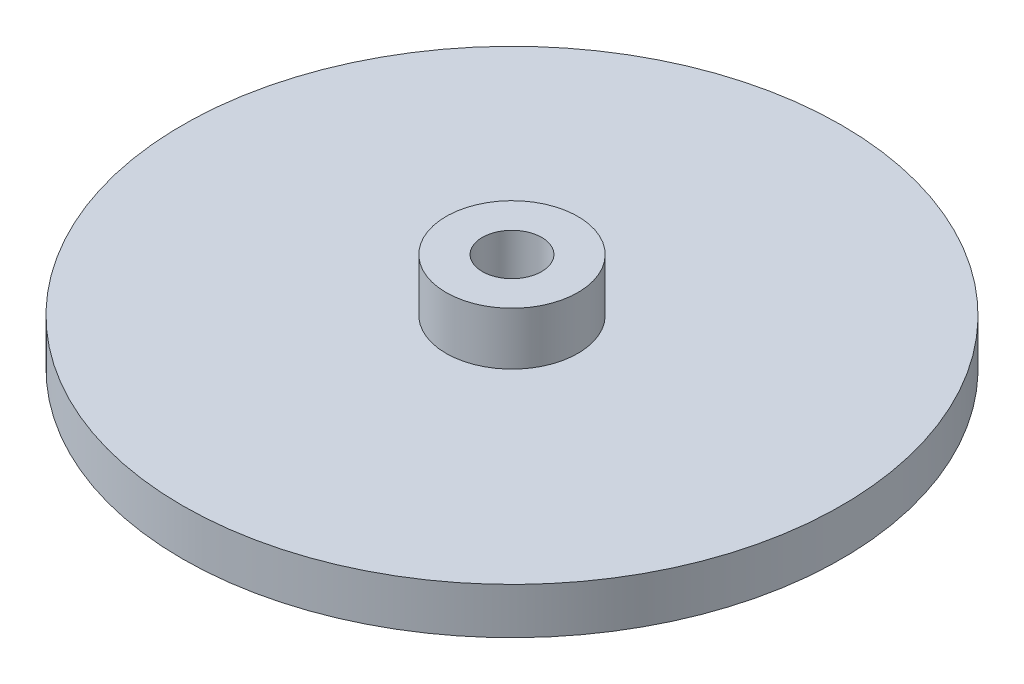
SolidWorks part; units mm, degrees
ref_plane "Front Plane" through (0, 0, 0) normal (0, 0, 1) x (1, 0, 0)
ref_plane "Top Plane" through (0, 0, 0) normal (0, 1, 0) x (1, 0, 0)
ref_plane "Right Plane" through (0, 0, 0) normal (1, 0, 0) x (0, 0, -1)
sketch "Sketch1" plane through (0, 0, 0) normal (0, 1, 0) x (1, 0, 0)
  circle A0 centre (0, 0) radius 25
  dimension "D1" = 50
extrude "Boss-Extrude1" add sketch "Sketch1" along normal blind 2
sketch "Sketch2" plane through (0, 2, 0) normal (0, 1, 0) x (1, 0, 0)
  circle A0 centre (0, 0) radius 5
  dimension "D1" = 10
extrude "Boss-Extrude2" add sketch "Sketch2" along normal blind 4
sketch "Sketch3" plane through (0, 0, 0) normal (0, -1, 0) x (1, 0, 0)
  circle A0 centre (0, 0) radius 2.1
  dimension "D1" = 4.2
extrude "Cut-Extrude1" cut sketch "Sketch3" against normal blind 20
sketch "Sketch4" plane through (0, 0, 0) normal (0, -1, 0) x (1, 0, 0)
  circle A0 centre (0, 0) radius 4.5
  dimension "D1" = 9
extrude "Cut-Extrude2" cut sketch "Sketch4" against normal blind 5
sketch "Sketch5" plane through (0, 5, 0) normal (0, -1, 0) x (1, 0, 0)
  circle A0 centre (0, 0) radius 2.25
  dimension "D1" = 4.5
extrude "Cut-Extrude3" cut sketch "Sketch5" against normal blind 10
sketch "Sketch6" plane through (0, 0, 0) normal (0, -1, 0) x (1, 0, 0)
  circle A0 centre (0, 0) radius 4.5
  circle A1 centre (0, 0) radius 25
  circle A2 centre (0, 0) radius 25
  circle A3 centre (0, 0) radius 25
  circle M2 centre (0, 0) radius 4.5
  circle M3 centre (0, 0) radius 25
  dimension "D1" = 0
extrude "Boss-Extrude3" add sketch "Sketch6" along normal blind 1.5 contours M3 M2
sketch "Sketch7" plane through (0, 5, 0) normal (0, -1, 0) x (1, 0, 0)
  circle A0 centre (0, 0) radius 2.25
  circle A1 centre (0, 0) radius 4.5
  circle A2 centre (0, 0) radius 4.5
  dimension "D1" = 0
extrude "Boss-Extrude5" add sketch "Sketch7" along normal blind 3.5 contours A2 | A0
